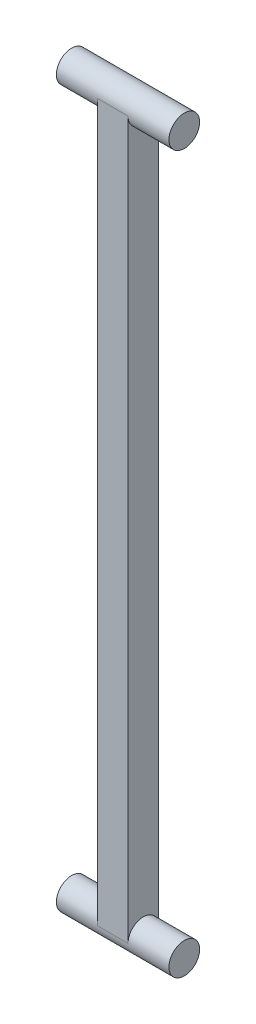
SolidWorks part; units mm, degrees
ref_plane "Front Plane" through (0, 0, 0) normal (0, 0, 1) x (1, 0, 0)
ref_plane "Top Plane" through (0, 0, 0) normal (0, 1, 0) x (1, 0, 0)
ref_plane "Right Plane" through (0, 0, 0) normal (1, 0, 0) x (0, 0, -1)
sketch "Sketch1" plane through (0, 0, 0) normal (0, 0, 1) x (1, 0, 0)
  line L1 (-15, 175) -> (15, 175)
  line L2 (-15, 175) -> (-15, -175)
  line L3 (-15, -175) -> (15, -175)
  line L4 (15, 175) -> (15, -175)
  line L5 (-15, 175) -> (15, -175) construction
  line L6 (-15, -175) -> (15, 175) construction
  point P0 (0, 0)
  dimension "D1" = 30
  dimension "D2" = 350
extrude "Boss-Extrude1" add sketch "Sketch1" along normal blind 30
sketch "Sketch2" plane through (15, 0, 0) normal (1, 0, 0) x (0, 0, -1)
  line L0 (-30, -175) -> (0, -175) construction
  circle A0 centre (-15, -175) radius 15
extrude "Boss-Extrude2" add sketch "Sketch2" along normal blind 40 and the other way blind 70
mirror "Mirror1" about plane through (-15, 175, 30) normal (0, -1, 0) of bodies 102
